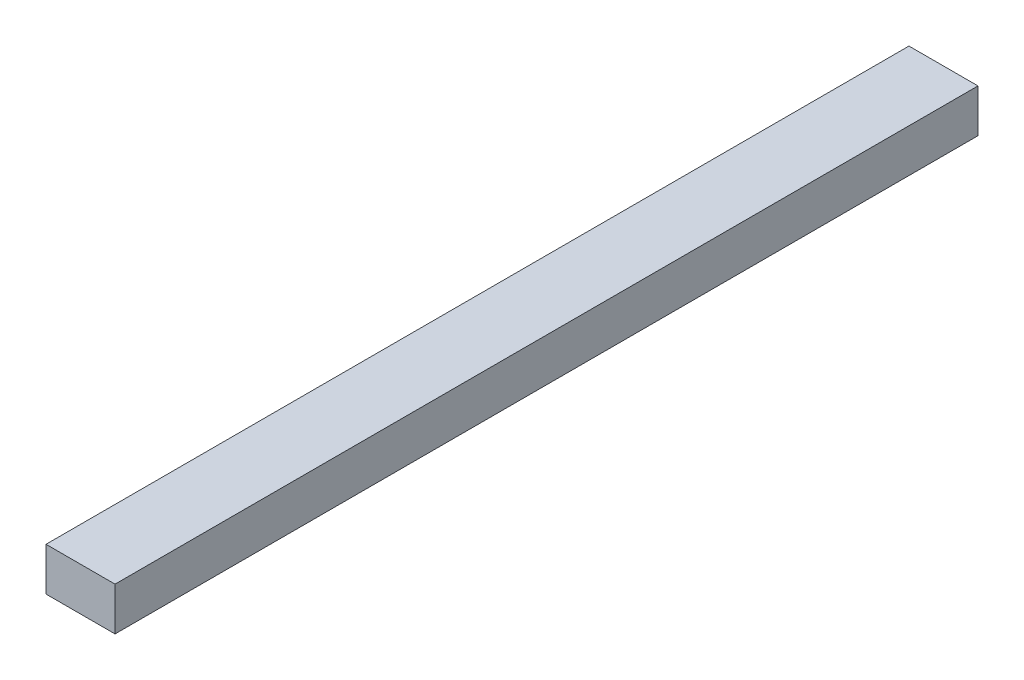
SolidWorks part; units mm, degrees
ref_plane "Plan de face" through (0, 0, 0) normal (0, 0, 1) x (1, 0, 0)
ref_plane "Plan de dessus" through (0, 0, 0) normal (0, 1, 0) x (1, 0, 0)
ref_plane "Plan de droite" through (0, 0, 0) normal (1, 0, 0) x (0, 0, -1)
sketch "Esquisse1" plane through (0, 0, 0) normal (0, 0, 1) x (1, 0, 0)
  line L1 (0, 0) -> (40, 0)
  line L2 (0, 0) -> (0, 25)
  line L3 (0, 25) -> (40, 25)
  line L4 (40, 0) -> (40, 25)
  dimension "D1" = 40
  dimension "D2" = 25
extrude "Boss.-Extru.1" add sketch "Esquisse1" along normal blind 500
